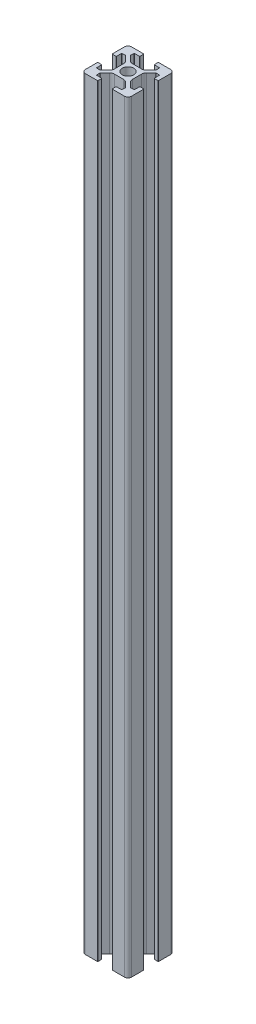
SolidWorks part; units mm, degrees
ref_plane "Front Plane" through (0, 0, 0) normal (0, 0, 1) x (1, 0, 0)
ref_plane "Top Plane" through (0, 0, 0) normal (0, 1, 0) x (1, 0, 0)
ref_plane "Right Plane" through (0, 0, 0) normal (1, 0, 0) x (0, 0, -1)
sketch "Sketch1" plane through (0, 0, 0) normal (0, 1, 0) x (1, 0, 0)
  line L0 (10, 20) -> (10, 10) construction
  line L1 (0, 0) -> (20, 0)
  line L2 (0, 0) -> (0, 20)
  line L3 (0, 20) -> (20, 20)
  line L4 (20, 0) -> (20, 20)
  line L5 (6.1, 13.9) -> (13.9, 13.9)
  line L6 (6.1, 13.9) -> (6.1, 6.1)
  line L7 (6.1, 6.1) -> (13.9, 6.1)
  line L8 (13.9, 13.9) -> (13.9, 6.1)
  line L9 (10, 10) -> (0, 10) construction
  line L10 (2.8607, 18.2) -> (18.2, 2.8607)
  line L11 (1.8, 18.2) -> (18.2, 18.2)
  line L12 (1.8, 18.2) -> (1.8, 1.8)
  line L13 (1.8, 1.8) -> (18.2, 1.8)
  line L14 (18.2, 18.2) -> (18.2, 1.8)
  line L15 (1.8, 17.1393) -> (17.1393, 1.8)
  line L16 (17.1393, 18.2) -> (1.8, 2.8607)
  line L17 (18.2, 17.1393) -> (2.8607, 1.8)
  line L18 (1.8, 18.2) -> (18.2, 1.8) construction
  line L19 (1.8, 17.1393) -> (2.3303, 17.6697) construction
  line L20 (2.3303, 17.6697) -> (2.8607, 18.2) construction
  line L21 (1.8, 1.8) -> (18.2, 18.2) construction
  line L22 (18.2, 1.8) -> (15.5, 1.8)
  line L23 (18.2, 1.8) -> (18.2, 4.5)
  line L24 (18.2, 4.5) -> (15.5, 4.5)
  line L25 (15.5, 1.8) -> (15.5, 4.5)
  line L26 (18.2, 13.1) -> (20, 13.1)
  line L27 (18.2, 18.2) -> (15.5, 18.2)
  line L28 (18.2, 18.2) -> (18.2, 15.5)
  line L29 (18.2, 15.5) -> (15.5, 15.5)
  line L30 (15.5, 18.2) -> (15.5, 15.5)
  line L31 (18.2, 6.9) -> (20, 6.9)
  line L32 (4.5, 18.2) -> (4.5, 15.5)
  line L33 (1.8, 15.5) -> (4.5, 15.5)
  line L34 (4.5, 1.8) -> (4.5, 4.5)
  line L35 (1.8, 4.5) -> (4.5, 4.5)
  line L36 (1.8, 6.9) -> (0, 6.9)
  line L37 (1.8, 13.1) -> (0, 13.1)
  line L38 (6.9, 20) -> (6.9, 18.2)
  line L39 (13.1, 20) -> (13.1, 18.2)
  line L40 (6.9, 0) -> (6.9, 1.8)
  line L41 (13.1, 0) -> (13.1, 1.8)
  circle A0 centre (10, 10) radius 2.5
  point P9 (10, 20)
  point P10 (10, 13.9)
  point P11 (0, 10)
  point P12 (6.1, 10)
  point P21 (10, 18.2)
  point P22 (1.8, 10)
  point P56 (0, 0)
  dimension "D3" = 5
  dimension "D1" = 20
  dimension "D2" = 6.1
  dimension "D4" = 1.5
  dimension "D5" = 1.5
  dimension "D6" = 1.8
  dimension "D7" = 11
  dimension "D8" = 6.2
  dimension "D9" = 6.9
  dimension "D10" = 6.2
  dimension "D11" = 6.9
extrude "Boss-Extrude1" add sketch "Sketch1" along normal blind 330 contours L38 L3 L2 L37 L12 L11 | L15 L33 L32 L10 L11 L12 | L32 L11 L10 | L12 L33 L15 | L33 L15 L6 L5 L10 L32 | L3 L39 L11 L14 L26 L4 | L11 L30 L16 | L16 L30 L29 L17 L14 L11 | L29 L14 L17 | L30 L16 L5 L8 L17 L29 | A0 L16 L5 L10 | A0 L10 L5 L6 L15 | A0 L17 L8 L5 L16 | A0 L10 L8 L17 | A0 L15 L6 L16 | A0 L16 L6 L7 L17 | A0 L17 L7 L15 | A0 L15 L7 L8 L10 | L16 L35 L34 L17 L7 L6 | L15 L25 L24 L10 L8 L7 | L35 L12 L16 | L35 L16 L12 L13 L17 L34 | L13 L34 L17 | L1 L40 L13 L12 L36 L2 | L14 L24 L10 | L25 L15 L13 L14 L10 L24 | L25 L13 L15 | L41 L1 L4 L31 L14 L13
fillet "Fillet1" radius 1.5 4 edges at (0, 165, -20) (0, 165, 0) (20, 165, -20) (20, 165, 0)
fillet "Fillet2" radius 0.2 32 edges at (6.9, 165, -1.8) (6.9, 165, 0) (0, 165, -6.9) (1.8, 165, -6.9) (1.8, 165, -4.5) (3.4393, 165, -4.5) (3.4393, 165, -15.5) (1.8, 165, -15.5) (1.8, 165, -13.1) (0, 165, -13.1) (6.9, 165, -20) (6.9, 165, -18.2) (4.5, 165, -18.2) (4.5, 165, -16.5607) (15.5, 165, -16.5607) (15.5, 165, -18.2) (13.1, 165, -18.2) (13.1, 165, -20) (20, 165, -13.1) (18.2, 165, -13.1) (18.2, 165, -15.5) (16.5607, 165, -15.5) (16.5607, 165, -4.5) (18.2, 165, -4.5) (18.2, 165, -6.9) (20, 165, -6.9) (13.1, 165, 0) (13.1, 165, -1.8) (15.5, 165, -1.8) (15.5, 165, -3.4393) (4.5, 165, -3.4393) (4.5, 165, -1.8)
fillet "Fillet3" radius 2 8 edges at (13.9, 165, -7.1607) (12.8393, 165, -6.1) (7.1607, 165, -6.1) (6.1, 165, -12.8393) (6.1, 165, -7.1607) (12.8393, 165, -13.9) (7.1607, 165, -13.9) (13.9, 165, -12.8393)
sketch "Sketch2" plane through (0, 0, -20) normal (0, 0, -1) x (-1, 0, 0)
  line L0 (-10, 330) -> (-10, 0) construction
  line L1 (-7.9891, 330) -> (-12.0109, 330) construction
  line L2 (-7.9891, 0) -> (-12.0109, 0) construction
  circle A0 centre (-10, 304) radius 2.1
  circle A1 centre (-10, 268) radius 2.1
  circle A2 centre (-10, 46) radius 2.1
  circle A3 centre (-10, 10) radius 2.1
  point P13 (0, 0)
  point P14 (0, 0)
  dimension "D3" = 4.2
  dimension "D1" = 36
  dimension "D2" = 26
  dimension "D4" = 10
  dimension "D5" = 36
extrude "Cut-Extrude1" cut sketch "Sketch2" against normal through all
